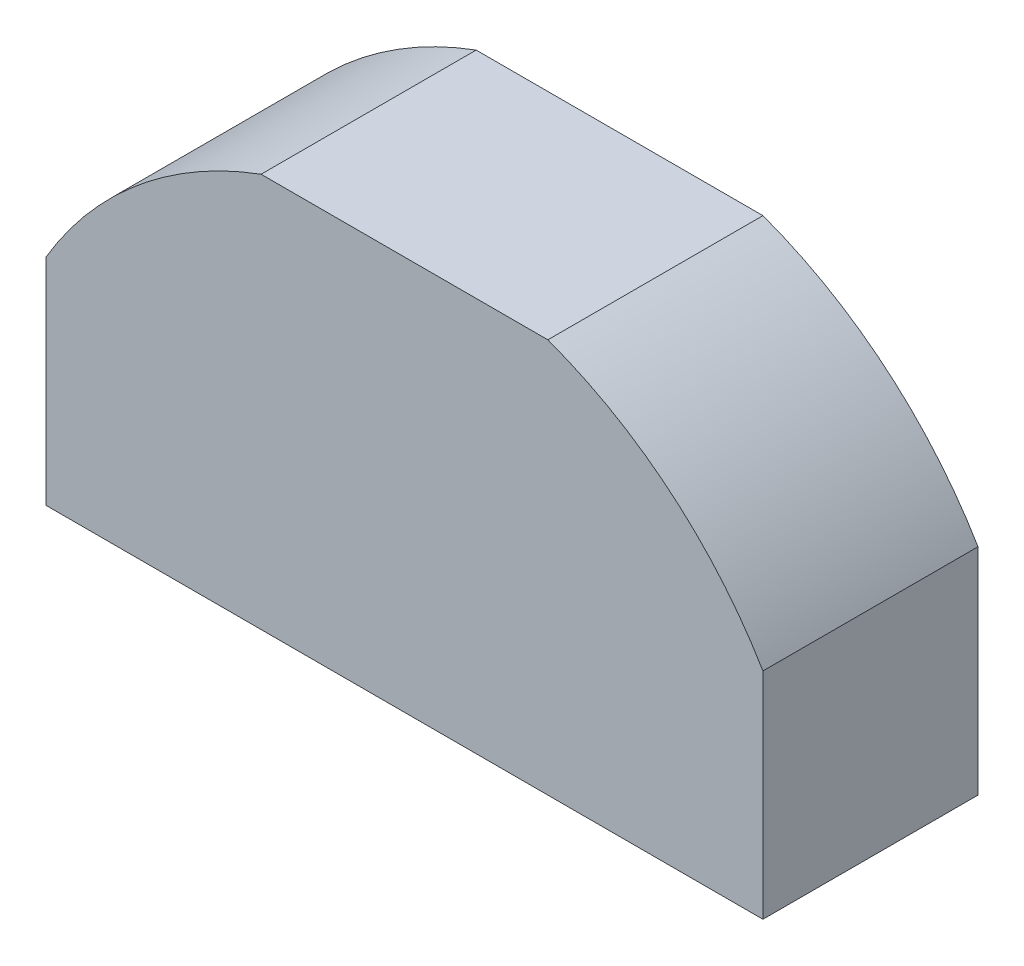
SolidWorks part; units mm, degrees
ref_plane "Front Plane" through (0, 0, 0) normal (0, 0, 1) x (1, 0, 0)
ref_plane "Top Plane" through (0, 0, 0) normal (0, 1, 0) x (1, 0, 0)
ref_plane "Right Plane" through (0, 0, 0) normal (1, 0, 0) x (0, 0, -1)
sketch "Sketch1" plane through (0, 0, 0) normal (0, 0, 1) x (1, 0, 0)
  line L0 (5, 0) -> (-5, 0)
  line L1 (-5, 0) -> (-5, 3)
  line L2 (0, 5.5) -> (0, 0.05) construction
  line L3 (2, 5.5) -> (-2, 5.5)
  line L4 (5, 0) -> (5, 3)
  arc A0 (-2, 5.5) -> (-5, 3) centre (0, 0.05) ccw
  arc A1 (2, 5.5) -> (5, 3) centre (0, 0.05) cw
  point P10 (0, 0)
  dimension "D1" = 3
  dimension "D2" = 10
  dimension "D3" = 5.5
  dimension "D4" = 2
extrude "Boss-Extrude1" add sketch "Sketch1" along normal blind 3
